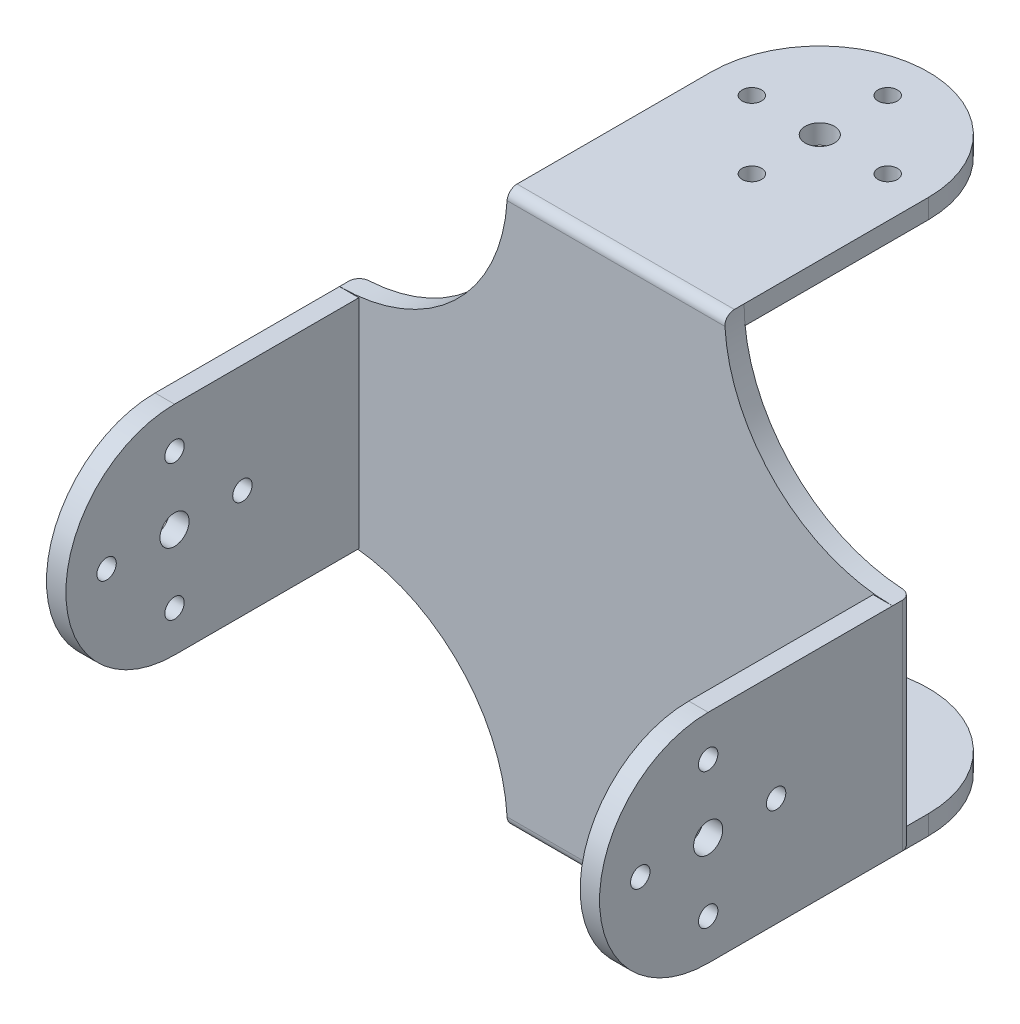
SolidWorks part; units mm, degrees
ref_plane "前视基准面" through (0, 0, 0) normal (0, 0, 1) x (1, 0, 0)
ref_plane "上视基准面" through (0, 0, 0) normal (0, 1, 0) x (1, 0, 0)
ref_plane "右视基准面" through (0, 0, 0) normal (1, 0, 0) x (0, 0, -1)
sketch "草图1" plane through (0, 0, 0) normal (0, 0, 1) x (1, 0, 0)
  line L0 (16.2645, 16.2645) -> (28.5, 28.5) construction
  line L1 (-11.1964, 28.5) -> (11.1964, 28.5)
  line L2 (-28.5, 11.1964) -> (-28.5, -11.1964)
  line L3 (-11.1964, -28.5) -> (11.1964, -28.5)
  line L4 (28.5, 11.1964) -> (28.5, -11.1964)
  line L5 (-28.5, 28.5) -> (-16.2645, 16.2645) construction
  line L6 (-28.5, -28.5) -> (-16.2645, -16.2645) construction
  line L7 (16.2645, -16.2645) -> (28.5, -28.5) construction
  arc A0 (-28.5, 11.1964) -> (-11.1964, 28.5) centre (-28.5, 28.5) ccw
  arc A1 (11.1964, 28.5) -> (28.5, 11.1964) centre (28.5, 28.5) ccw
  arc A2 (-11.1964, -28.5) -> (-28.5, -11.1964) centre (-28.5, -28.5) ccw
  arc A3 (28.5, -11.1964) -> (11.1964, -28.5) centre (28.5, -28.5) ccw
  point P0 (0, 0)
  dimension "D1" = 57
  dimension "D2" = 57
extrude "凸台-拉伸3" add sketch "草图1" along normal blind 2
sketch "草图12" plane through (0, 28.5, 0) normal (0, 1, 0) x (1, 0, 0)
  line L0 (-11.1964, -2) -> (-11.1964, 19)
  line L1 (11.1964, -2) -> (11.1964, 19)
  line L2 (-11.1964, -2) -> (11.1964, -2)
  arc A0 (11.1964, 19) -> (-11.1964, 19) centre (0, 19) ccw
extrude "凸台-拉伸8" add sketch "草图12" against normal blind 2
mirror "镜向6" about plane through (0, 0, 0) normal (0, 1, 0) of "凸台-拉伸8"
sketch "草图13" plane through (28.5, 0, 0) normal (1, 0, 0) x (0, 0, -1)
  line L0 (0, 11.1964) -> (-21, 11.1964)
  line L1 (0, -11.1964) -> (-21, -11.1964)
  line L2 (0, 11.1964) -> (0, -11.1964)
  arc A0 (-21, 11.1964) -> (-21, -11.1964) centre (-21, 0) ccw
extrude "凸台-拉伸9" add sketch "草图13" against normal blind 2
mirror "镜向7" about plane through (0, 0, 0) normal (1, 0, 0) of "凸台-拉伸9"
sketch "草图14" plane through (-28.5, 0, 0) normal (-1, 0, 0) x (0, 0, 1)
  circle A0 centre (21, 0) radius 1.5
  circle A2 centre (21, 7) radius 1
  circle A3 centre (28, 0) radius 1
  circle A4 centre (21, -7) radius 1
  circle A5 centre (14, 0) radius 1
  point P15 (21, 0)
  dimension "D1" = 4
extrude "切除-拉伸4" cut sketch "草图14" against normal through all
sketch "草图15" plane through (0, -28.5, 0) normal (0, -1, 0) x (1, 0, 0)
  circle A0 centre (0, -19) radius 1.5
  circle A2 centre (0, -12) radius 1
  circle A3 centre (7, -19) radius 1
  circle A4 centre (0, -26) radius 1
  circle A5 centre (-7, -19) radius 1
  point P15 (0, -19)
  dimension "D1" = 4
extrude "切除-拉伸5" cut sketch "草图15" against normal through all
fillet "圆角9" radius 1 1 edges at (-28.5, 0, 0)
fillet "圆角10" radius 1 1 edges at (28.5, 0, 0)
fillet "圆角11" radius 1 1 edges at (0, -28.5, 2)
fillet "圆角12" radius 1 1 edges at (0, 28.5, 2)
